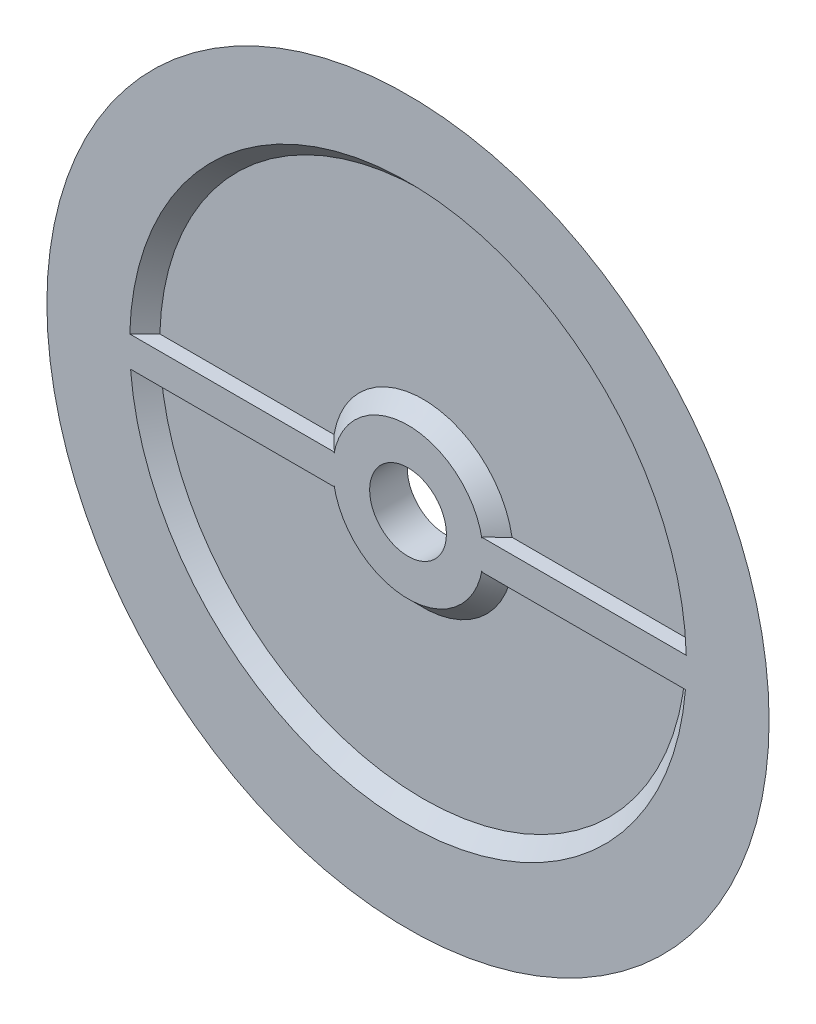
SolidWorks part; units mm, degrees
material "아크릴(내충격성)"
ref_plane "정면" through (0, 0, 0) normal (0, 0, 1) x (1, 0, 0)
ref_plane "윗면" through (0, 0, 0) normal (0, 1, 0) x (1, 0, 0)
ref_plane "우측면" through (0, 0, 0) normal (1, 0, 0) x (0, 0, -1)
sketch "스케치1" plane through (0, 0, 0) normal (0, 0, 1) x (1, 0, 0)
  circle A0 centre (0, 0) radius 37
  dimension "D1" = 74
extrude "보스-돌출1" add sketch "스케치1" along normal blind 5
ref_plane "평면1" through (0, 0, 2.5) normal (0, 0, 1) x (1, 0, 0)
sketch "스케치3" plane through (0, 0, 0) normal (0, 1, 0) x (1, 0, 0)
  line L0 (-37, -5) -> (-37, 0)
  line L1 (-37, 0) -> (-48, -5)
  line L2 (-48, -5) -> (-37, -5)
  line L3 (0, 6.4626) -> (0, -29.948) construction
  dimension "D1" = 11
revolve "회전1" add sketch "스케치3" angle 360 about L3
sketch "스케치4" plane through (0, 0, 0) normal (0, 0, -1) x (-1, 0, 0)
  circle A0 centre (0, 0) radius 34.4
  circle A1 centre (0, 0) radius 30.4
  circle A2 centre (0, 0) radius 37 construction
  dimension "D1" = 4
  dimension "D2" = 2.6
extrude "보스-돌출2" add sketch "스케치4" along normal blind 0.8
sketch "스케치5" plane through (0, 0, 0) normal (0, 0, -1) x (-1, 0, 0)
  circle A0 centre (0, 0) radius 5.1
  dimension "D1" = 10.2
extrude "컷-돌출1" cut sketch "스케치5" against normal through all contours A0
sketch "스케치6" plane through (0, 0, 5) normal (0, 0, 1) x (1, 0, 0)
  circle A0 centre (0, 0) radius 10
  circle A1 centre (0, 0.9905) radius 37
  dimension "D1" = 74
  dimension "D2" = 20
extrude "컷-돌출2" cut sketch "스케치6" against normal blind 2 draft 45
sketch "스케치7" plane through (0, 0, 5) normal (0, 0, 1) x (1, 0, 0)
  line L1 (-40.1871, 2) -> (-14.8661, 2)
  line L2 (-40.1871, 2) -> (-40.1871, -2)
  line L3 (-40.1871, -2) -> (-14.8661, -2)
  line L4 (-14.8661, 2) -> (-14.8661, -2)
  line L5 (-40.1871, 2) -> (-14.8661, -2) construction
  line L6 (-40.1871, -2) -> (-14.8661, 2) construction
  circle A1 centre (0, 0) radius 15 construction
  point P0 (-27.5266, 0)
  dimension "D1" = 4
extrude "보스-돌출3" add sketch "스케치7" against normal blind 2
sketch "스케치9" plane through (-14.8661, 0, 0) normal (1, 0, 0) x (0, 0, -1)
  line L1 (-5, 2) -> (-3, 2)
  line L2 (-5, 2) -> (-5, -2)
  line L3 (-5, -2) -> (-3, -2)
  line L4 (-3, 2) -> (-3, -2)
extrude "보스-돌출5" add sketch "스케치9" along normal blind 5
sketch "스케치10" plane through (0, 0, 0) normal (1, 0, 0) x (0, 0, -1)
  line L0 (37.3425, 0) -> (-26.3325, 0) construction
pattern_circular "원형 패턴1" count 2 over 360 about axis through (0, 0, 0) along (0, 0, 1) of "보스-돌출3", "보스-돌출5"
